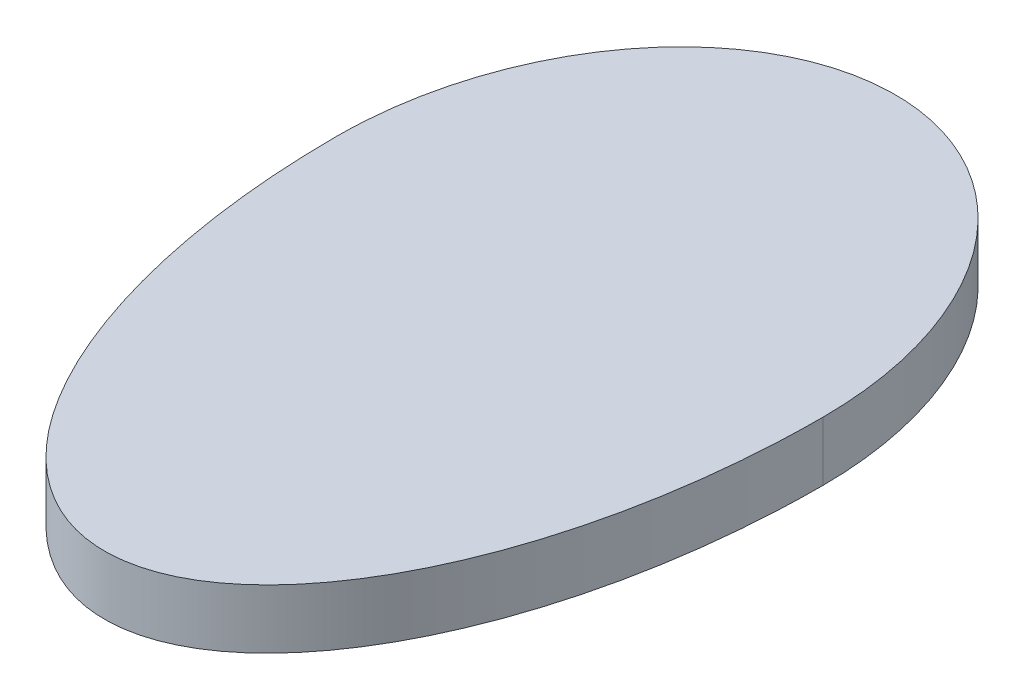
SolidWorks part; units mm, degrees
ref_plane "Front Plane" through (0, 0, 0) normal (0, 0, 1) x (1, 0, 0)
ref_plane "Top Plane" through (0, 0, 0) normal (0, 1, 0) x (1, 0, 0)
ref_plane "Right Plane" through (0, 0, 0) normal (1, 0, 0) x (0, 0, -1)
sketch "midlines" plane through (0, 0, 0) normal (0, 1, 0) x (1, 0, 0)
  line L0 (0, 0) -> (0, 106.76) construction
  line L1 (0, 0) -> (0, -160.73) construction
  line L2 (82.28, 0) -> (-82.28, 0) construction
  point P7 (0, 0)
  dimension "D1" = 106.76
  dimension "D2" = 160.73
  dimension "D3" = 164.56
sketch "Sketch4" plane through (0, 0, 0) normal (0, 1, 0) x (1, 0, 0)
  ellipse E0 centre (0, 0) end of major axis (0, 106.76) minor radius 82.28 (82.28, 0) -> (-82.28, 0) ccw
  ellipse E1 centre (0, 0) end of major axis (0, -160.73) minor radius 82.28 (82.28, 0) -> (-82.28, 0) cw
extrude "Boss-Extrude1" add sketch "Sketch4" along normal blind 20
